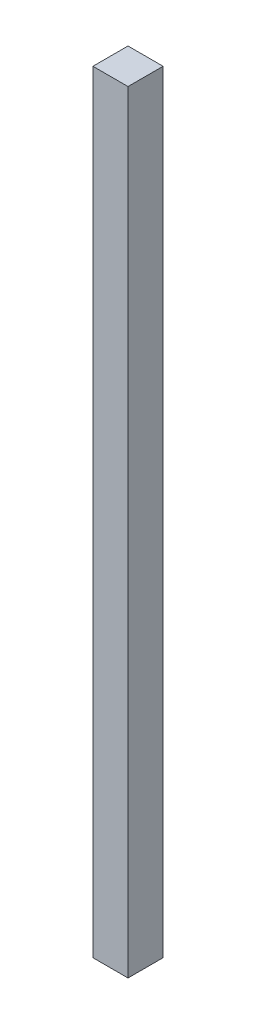
SolidWorks part; units mm, degrees
ref_plane "Front Plane" through (0, 0, 0) normal (0, 0, 1) x (1, 0, 0)
ref_plane "Top Plane" through (0, 0, 0) normal (0, 1, 0) x (1, 0, 0)
ref_plane "Right Plane" through (0, 0, 0) normal (1, 0, 0) x (0, 0, -1)
sketch "Sketch1" plane through (0, 0, 0) normal (0, 1, 0) x (1, 0, 0)
  line L1 (0, 0) -> (-25, 0)
  line L2 (0, 0) -> (0, -25)
  line L3 (0, -25) -> (-25, -25)
  line L4 (-25, 0) -> (-25, -25)
  dimension "D1" = 25
  dimension "D2" = 25
extrude "Boss-Extrude1" add sketch "Sketch1" along normal blind 550 contours L1 L4 L3 L2
